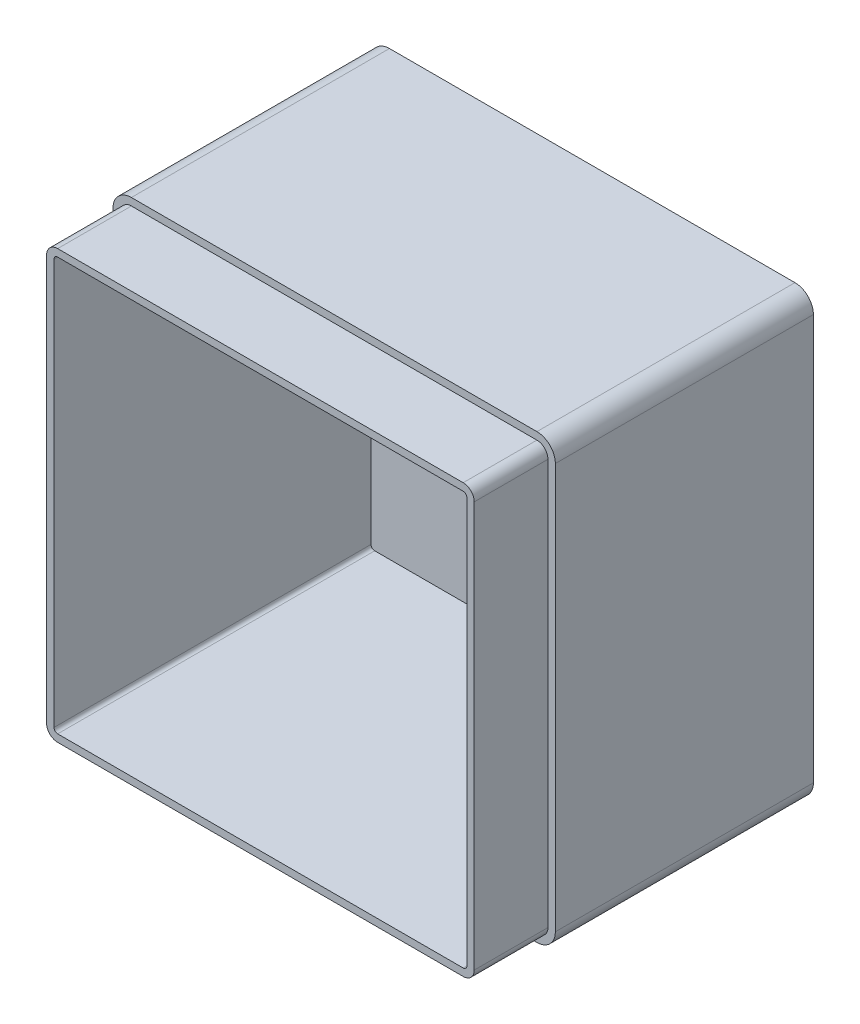
SolidWorks part; units mm, degrees
ref_plane "Front Plane" through (0, 0, 0) normal (0, 0, 1) x (1, 0, 0)
ref_plane "Top Plane" through (0, 0, 0) normal (0, 1, 0) x (1, 0, 0)
ref_plane "Right Plane" through (0, 0, 0) normal (1, 0, 0) x (0, 0, -1)
sketch "Sketch1" plane through (0, 0, 0) normal (0, 0, 1) x (1, 0, 0)
  line L1 (0, 0) -> (120, 0)
  line L2 (0, 0) -> (0, 120)
  line L3 (0, 120) -> (120, 120)
  line L4 (120, 0) -> (120, 120)
  dimension "D1" = 120
  dimension "D2" = 120
extrude "Boss-Extrude1" add sketch "Sketch1" along normal blind 90
fillet "Fillet1" radius 5 4 edges at (0, 0, 45) (120, 0, 45) (120, 120, 45) (0, 120, 45)
shell "Shell1" thickness 4
sketch "Sketch2" plane through (0, 0, 90) normal (0, 0, 1) x (1, 0, 0)
  line L4 (0, 115) -> (0, 5)
  line L5 (5, 0) -> (115, 0)
  line L6 (120, 5) -> (120, 115)
  line L7 (115, 120) -> (5, 120)
  line L8 (0, 115) -> (0, 5)
  line L9 (5, 0) -> (115, 0)
  line L10 (120, 5) -> (120, 115)
  line L11 (115, 120) -> (5, 120)
  arc A4 (0, 5) -> (5, 0) centre (5, 5) ccw
  arc A5 (115, 0) -> (120, 5) centre (115, 5) ccw
  arc A6 (120, 115) -> (115, 120) centre (115, 115) ccw
  arc A7 (5, 120) -> (0, 115) centre (5, 115) ccw
  arc A8 (0, 5) -> (5, 0) centre (5, 5) ccw
  arc A9 (115, 0) -> (120, 5) centre (115, 5) ccw
  arc A10 (120, 115) -> (115, 120) centre (115, 115) ccw
  arc A11 (5, 120) -> (0, 115) centre (5, 115) ccw
  dimension "D1" = 0
sketch "Sketch3" plane through (0, 0, 90) normal (0, 0, 1) x (1, 0, 0)
  line L0 (2, 115) -> (2, 5)
  line L1 (5, 2) -> (115, 2)
  line L2 (118, 5) -> (118, 115)
  line L3 (115, 118) -> (5, 118)
  line L4 (0, 115) -> (0, 5)
  line L5 (5, 0) -> (115, 0)
  line L6 (120, 5) -> (120, 115)
  line L7 (115, 120) -> (5, 120)
  line L8 (0, 115) -> (0, 5)
  line L9 (5, 0) -> (115, 0)
  line L10 (120, 5) -> (120, 115)
  line L11 (115, 120) -> (5, 120)
  arc A0 (2, 5) -> (5, 2) centre (5, 5) ccw
  arc A1 (115, 2) -> (118, 5) centre (115, 5) ccw
  arc A2 (118, 115) -> (115, 118) centre (115, 115) ccw
  arc A3 (5, 118) -> (2, 115) centre (5, 115) ccw
  arc A4 (0, 5) -> (5, 0) centre (5, 5) ccw
  arc A5 (115, 0) -> (120, 5) centre (115, 5) ccw
  arc A6 (120, 115) -> (115, 120) centre (115, 115) ccw
  arc A7 (5, 120) -> (0, 115) centre (5, 115) ccw
  arc A8 (0, 5) -> (5, 0) centre (5, 5) ccw
  arc A9 (115, 0) -> (120, 5) centre (115, 5) ccw
  arc A10 (120, 115) -> (115, 120) centre (115, 115) ccw
  arc A11 (5, 120) -> (0, 115) centre (5, 115) ccw
  dimension "D1" = 0
  dimension "D2" = 2
extrude "Cut-Extrude1" cut sketch "Sketch3" against normal blind 20
